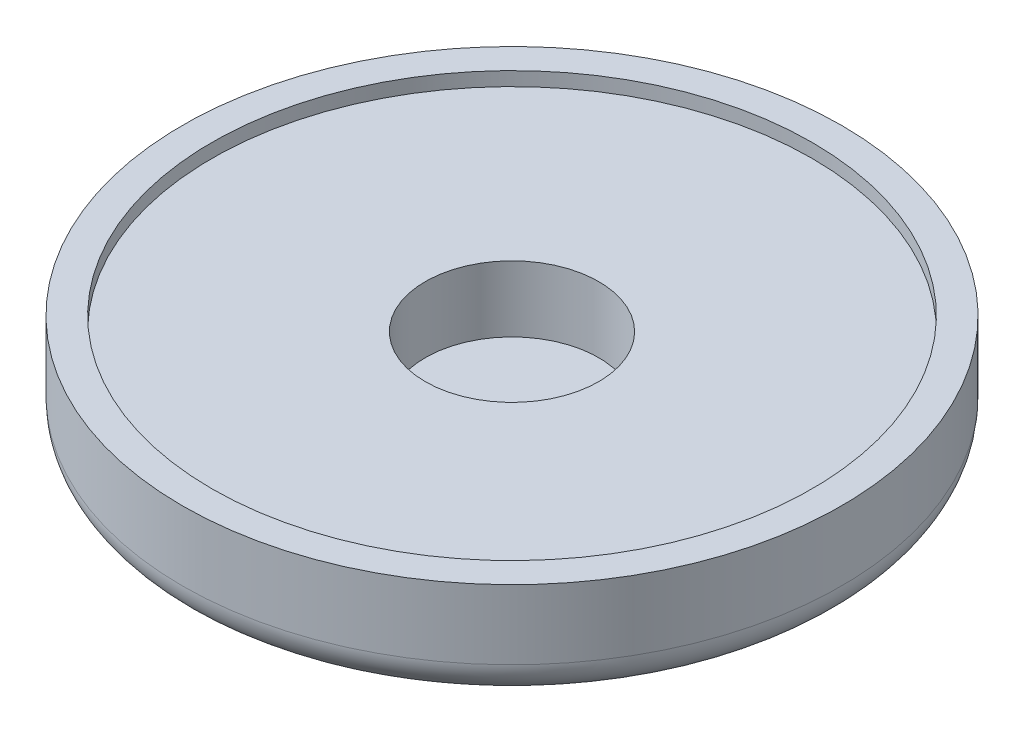
SolidWorks part; units mm, degrees
ref_plane "Front Plane" through (0, 0, 0) normal (0, 0, 1) x (1, 0, 0)
ref_plane "Top Plane" through (0, 0, 0) normal (0, 1, 0) x (1, 0, 0)
ref_plane "Right Plane" through (0, 0, 0) normal (1, 0, 0) x (0, 0, -1)
sketch "Sketch2" plane through (0, 0, 0) normal (0, 1, 0) x (1, 0, 0)
  circle A0 centre (0, 0) radius 24.13
extrude "Boss-Extrude1" add sketch "Sketch2" along normal blind 7.62
sketch "Sketch3" plane through (0, 7.62, 0) normal (0, 1, 0) x (1, 0, 0)
  circle A0 centre (0, 0) radius 21.971
extrude "Cut-Extrude1" cut sketch "Sketch3" against normal blind 1.016
sketch "Sketch4" plane through (0, 6.604, 0) normal (0, 1, 0) x (1, 0, 0)
  circle A0 centre (0, 0) radius 6.35
extrude "Cut-Extrude2" cut sketch "Sketch4" against normal blind 4.826
fillet "Fillet1" radius 2.54 1 edges at (0, 0, 24.13)
